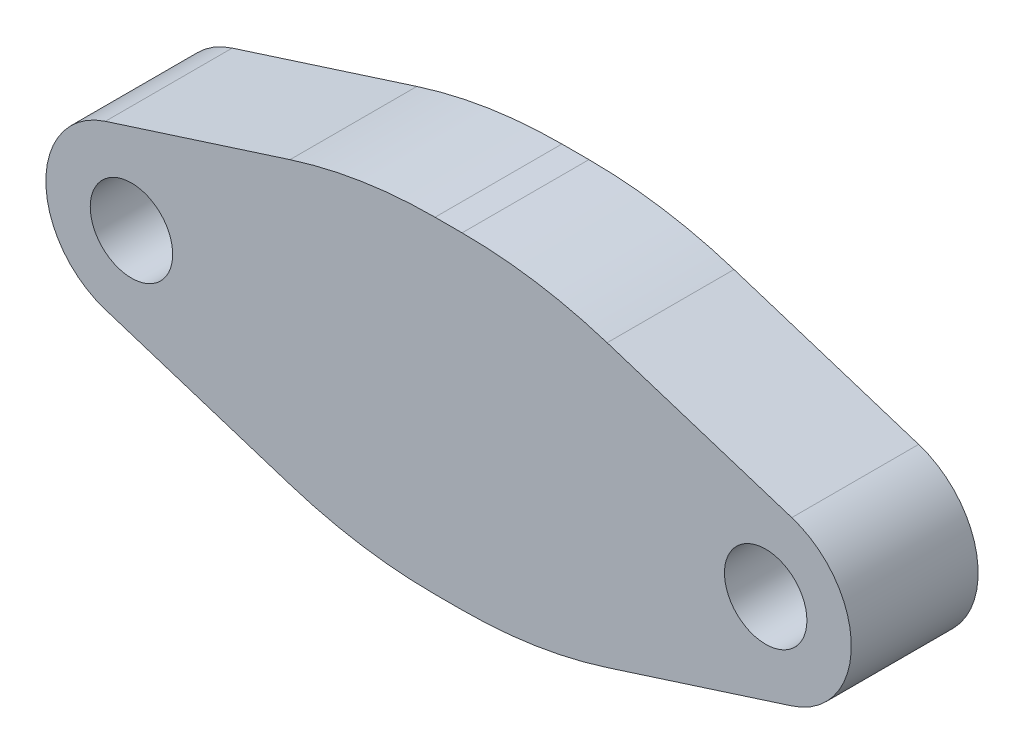
SolidWorks part; units mm, degrees
ref_plane "Front Plane" through (0, 0, 0) normal (0, 0, 1) x (1, 0, 0)
ref_plane "Top Plane" through (0, 0, 0) normal (0, 1, 0) x (1, 0, 0)
ref_plane "Right Plane" through (0, 0, 0) normal (1, 0, 0) x (0, 0, -1)
sketch "Sketch1" plane through (0, 0, 0) normal (0, 0, 1) x (1, 0, 0)
  line L0 (55, 0) -> (-55, 0) construction
  line L1 (10.8232, 2.5714) -> (5, 4.4357)
  line L2 (0.4264, 5.15) -> (-0.4264, 5.15)
  line L3 (0, -55) -> (0, 55) construction
  line L4 (-4.3301, 0) -> (4.3301, 0) construction
  line L5 (2.1651, 3.75) -> (-2.1651, 3.75)
  line L6 (-2.1651, 3.75) -> (-4.3301, 0)
  line L7 (-4.3301, 0) -> (-2.1651, -3.75)
  line L8 (-2.1651, -3.75) -> (2.1651, -3.75)
  line L9 (2.1651, -3.75) -> (4.3301, 0)
  line L10 (4.3301, 0) -> (2.1651, 3.75)
  line L11 (0.4264, -5.15) -> (-0.4264, -5.15)
  line L12 (10.8232, -2.5714) -> (5, -4.4357)
  line L13 (0, 0) -> (0, 3.75) construction
  line L14 (-10.8232, -2.5714) -> (-5, -4.4357)
  line L15 (-10.8232, 2.5714) -> (-5, 4.4357)
  arc A0 (10.8232, -2.5714) -> (10.8232, 2.5714) centre (10, 0) ccw
  arc A1 (5, 4.4357) -> (0.4264, 5.15) centre (0.4264, -9.85) ccw
  circle A2 centre (10, 0) radius 1.3
  circle A3 centre (0, 0) radius 3.75 construction
  arc A4 (5, -4.4357) -> (0.4264, -5.15) centre (0.4264, 9.85) cw
  arc A5 (-5, -4.4357) -> (-0.4264, -5.15) centre (-0.4264, 9.85) ccw
  arc A6 (-10.8232, -2.5714) -> (-10.8232, 2.5714) centre (-10, 0) cw
  arc A7 (-5, 4.4357) -> (-0.4264, 5.15) centre (-0.4264, -9.85) cw
  circle A8 centre (-10, 0) radius 1.3
  point P27 (0, -5.15)
  point P35 (0, 5.15)
  dimension "D1" = 2.6
  dimension "D2" = 1.4
  dimension "D4" = 15
  dimension "D3" = 10
  dimension "D5" = 5
  dimension "D6" = 1.4
  dimension "D7" = 7.5
extrude "Boss-Extrude1" add sketch "Sketch1" along normal blind 4
sketch "Sketch2" plane through (0, 0, 4) normal (0, 0, 1) x (1, 0, 0)
  circle A0 centre (0, 0) radius 4.3301
extrude "Boss-Extrude2" add sketch "Sketch2" against normal blind 1.2
